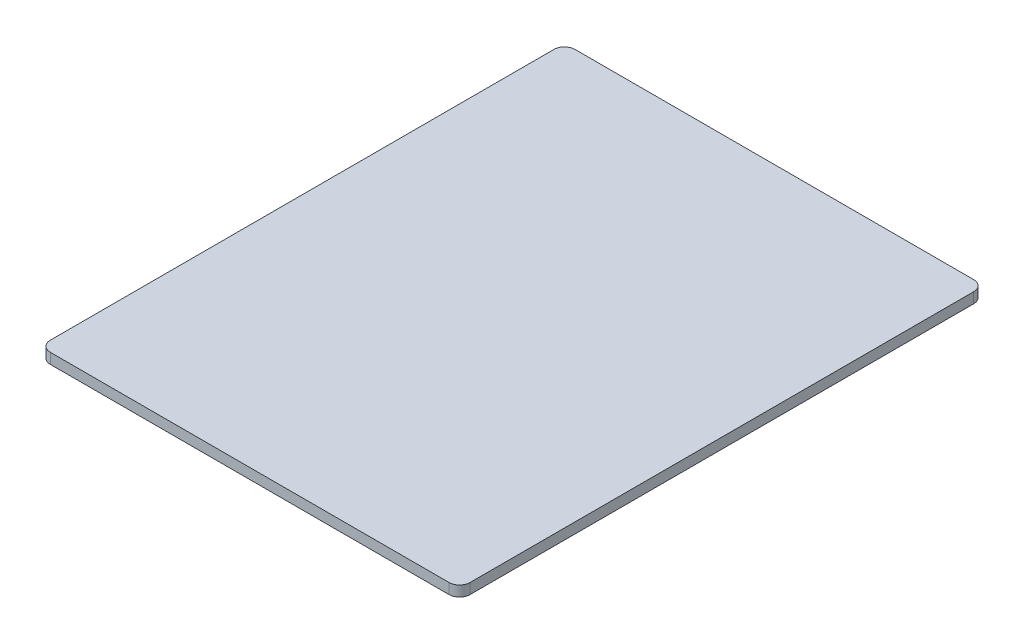
SolidWorks part; units mm, degrees
ref_plane "Front Plane" through (0, 0, 0) normal (0, 0, 1) x (1, 0, 0)
ref_plane "Top Plane" through (0, 0, 0) normal (0, 1, 0) x (1, 0, 0)
ref_plane "Right Plane" through (0, 0, 0) normal (1, 0, 0) x (0, 0, -1)
sketch "Sketch1" plane through (0, 0, 0) normal (0, 1, 0) x (1, 0, 0)
  line L1 (0, 0) -> (400, 0)
  line L2 (0, 0) -> (0, 500)
  line L3 (0, 500) -> (400, 500)
  line L4 (400, 0) -> (400, 500)
  dimension "D1" = 500
  dimension "D2" = 400
extrude "Boss-Extrude1" add sketch "Sketch1" along normal blind 10
sketch "Sketch2" plane through (0, 10, 0) normal (0, 1, 0) x (1, 0, 0)
  line L0 (400, 500) -> (0, 500) construction
  point P0 (200, 500)
fillet "Fillet1" radius 10 4 edges at (0, 5, -500) (400, 5, -500) (0, 5, 0) (400, 5, 0)
